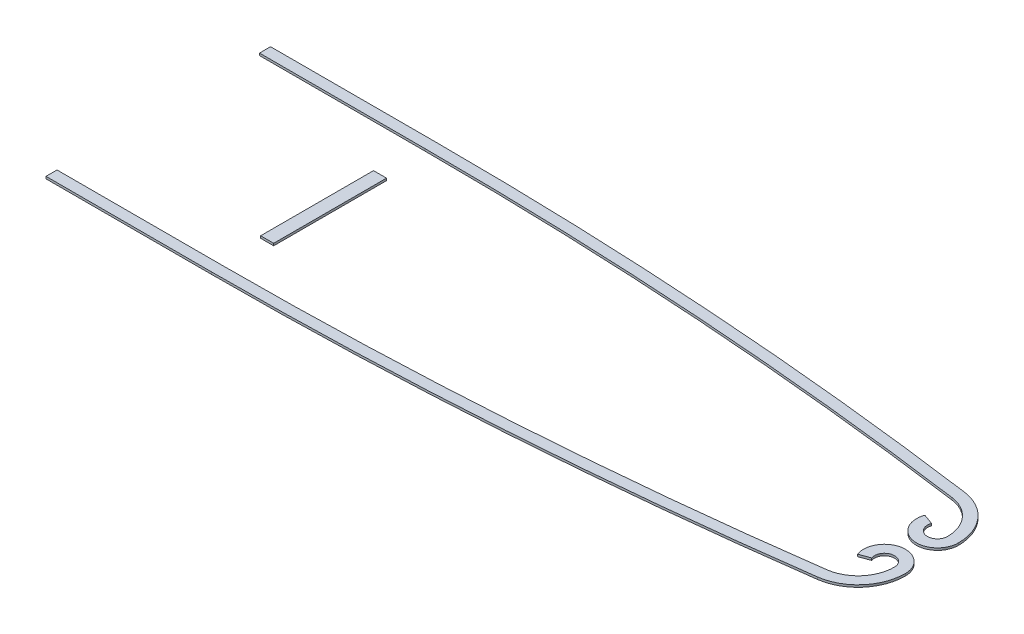
SolidWorks part; units mm, degrees
ref_plane "Front Plane" through (0, 0, 0) normal (0, 0, 1) x (1, 0, 0)
ref_plane "Top Plane" through (0, 0, 0) normal (0, 1, 0) x (1, 0, 0)
ref_plane "Right Plane" through (0, 0, 0) normal (1, 0, 0) x (0, 0, -1)
sketch "Sketch1" plane through (0, 0, 0) normal (0, 1, 0) x (1, 0, 0)
  line L0 (0, 50.9319) -> (-75, 50.9319)
  line L1 (0, 0) -> (224.4913, 0) construction
  line L2 (0, 45.9319) -> (-75, 45.9319)
  line L3 (-75, 50.9319) -> (-75, 45.9319)
  line L4 (262.2278, 13.5724) -> (257.5293, 15.2823)
  line L5 (262.2278, -13.5724) -> (257.5293, -15.2823)
  line L6 (-75, -50.9319) -> (-75, -45.9319)
  line L7 (0, -45.9319) -> (-75, -45.9319)
  line L8 (0, -50.9319) -> (-75, -50.9319)
  line L10 (-2.955, -25.6) -> (2.955, -25.6)
  line L11 (-2.955, -25.6) -> (-2.955, 25.6)
  line L12 (-2.955, 25.6) -> (2.955, 25.6)
  line L13 (2.955, -25.6) -> (2.955, 25.6)
  line L14 (-2.955, -25.6) -> (2.955, 25.6) construction
  line L15 (-2.955, 25.6) -> (2.955, -25.6) construction
  arc A1 (0, 50.9319) -> (257.431, 33.3261) centre (0, -1839.9431) cw
  arc A2 (257.431, 33.3261) -> (276.005, 12.025) centre (254.5037, 12.025) cw
  arc A3 (276.005, 12.025) -> (257.5293, 15.2823) centre (266.48, 12.025) cw
  arc A4 (271.005, 12.025) -> (262.2278, 13.5724) centre (266.48, 12.025) cw
  arc A5 (256.7502, 28.3727) -> (271.005, 12.025) centre (254.5037, 12.025) cw
  arc A6 (0, 45.9319) -> (256.7502, 28.3727) centre (0, -1839.9431) cw
  arc A7 (276.005, -12.025) -> (257.5293, -15.2823) centre (266.48, -12.025) ccw
  arc A8 (271.005, -12.025) -> (262.2278, -13.5724) centre (266.48, -12.025) ccw
  arc A9 (256.7502, -28.3727) -> (271.005, -12.025) centre (254.5037, -12.025) ccw
  arc A10 (257.431, -33.3261) -> (276.005, -12.025) centre (254.5037, -12.025) ccw
  arc A11 (0, -45.9319) -> (256.7502, -28.3727) centre (0, 1839.9431) ccw
  arc A12 (0, -50.9319) -> (257.431, -33.3261) centre (0, 1839.9431) ccw
  point P13 (256.955, 12.025)
  point P14 (2.955, 0)
  point P15 (266.48, 2.5)
  point P17 (0, 22.3)
  point P19 (276.005, 12.025)
  dimension "D1" = 23.6319
  dimension "D5" = 9.525
  dimension "D2" = 5
  dimension "D3" = 75
  dimension "D4" = 254
  dimension "D6" = 5
  dimension "D7" = 51.2
  dimension "D8" = 5.91
extrude "Boss-Extrude1" add sketch "Sketch1" along normal mid plane 1
